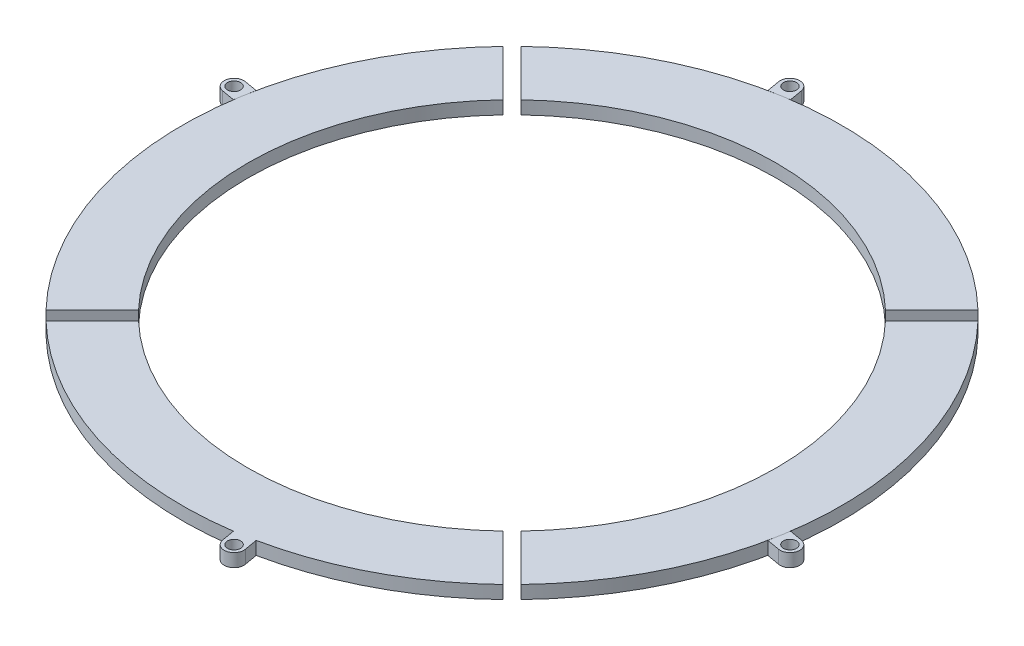
SolidWorks part; units mm, degrees
ref_plane "前视基准面" through (0, 0, 0) normal (0, 0, 1) x (1, 0, 0)
ref_plane "上视基准面" through (0, 0, 0) normal (0, 1, 0) x (1, 0, 0)
ref_plane "右视基准面" through (0, 0, 0) normal (1, 0, 0) x (0, 0, -1)
sketch "草图1" plane through (0, 0, 0) normal (0, 1, 0) x (1, 0, 0)
  line L0 (0, 28.5318) -> (0, -43.5615) construction
  line L1 (-12.686, 12.686) -> (30.0127, -30.0127) construction
  line L2 (0.7071, -0.7071) -> (71.4178, 70.0036)
  line L3 (71.4178, 70.0036) -> (70.0036, 71.4178)
  line L4 (70.0036, 71.4178) -> (-0.7071, 0.7071)
  line L5 (-0.7071, 0.7071) -> (0.7071, -0.7071)
  line L6 (0.7071, 0.7071) -> (-0.7071, -0.7071)
  line L7 (-0.7071, -0.7071) -> (70.0036, -71.4178)
  line L8 (70.0036, -71.4178) -> (71.4178, -70.0036)
  line L9 (71.4178, -70.0036) -> (0.7071, 0.7071)
  line L10 (0.7071, -0.7071) -> (-0.7071, 0.7071)
  line L11 (-0.7071, 0.7071) -> (-71.4178, -70.0036)
  line L12 (-71.4178, -70.0036) -> (-70.0036, -71.4178)
  line L13 (-70.0036, -71.4178) -> (0.7071, -0.7071)
  line L14 (-0.7071, -0.7071) -> (0.7071, 0.7071)
  line L15 (0.7071, 0.7071) -> (-70.0036, 71.4178)
  line L16 (-70.0036, 71.4178) -> (-71.4178, 70.0036)
  line L17 (-71.4178, 70.0036) -> (-0.7071, -0.7071)
  circle A0 centre (0, 0) radius 40.4
  circle A1 centre (0, 0) radius 50.4
  point P10 (0, 0)
  point P28 (0, 0)
  dimension "D2" = 80.8
  dimension "D3" = 100.8
  dimension "D1" = 45
  dimension "D4" = 100
  dimension "D5" = 2
  dimension "D6" = 4
extrude "凸台-拉伸1" add sketch "草图1" along normal blind 2 contours L17 A1 L11 A0 | L4 A1 L15 A0 | L9 A1 L2 A0 | L13 A1 L7 A0
sketch "草图2" plane through (0, 0, 0) normal (0, -1, 0) x (1, 0, 0)
  line L2 (0, 0) -> (9.0992, 51.6039) construction
  line L3 (10.2252, 49.3519) -> (7.2708, 49.8728)
  line L4 (8.3898, 8.3898) -> (0, 0) construction
  line L5 (27.8513, -29.2655) -> (29.2655, -27.8513) construction
  line L9 (0, 0) -> (10.8745, -10.8745) construction
  line L10 (7.2708, 49.8728) -> (7.622, 51.8644)
  line L17 (27.8513, 29.2655) -> (29.2655, 27.8513) construction
  line L18 (10.2252, 49.3519) -> (10.5764, 51.3435)
  line L19 (49.3519, 10.2252) -> (51.3435, 10.5764)
  line L20 (49.8728, 7.2708) -> (51.8644, 7.622)
  line L21 (49.3519, 10.2252) -> (49.8728, 7.2708)
  line L22 (-49.3519, -10.2252) -> (-51.3435, -10.5764)
  line L23 (-49.8728, -7.2708) -> (-51.8644, -7.622)
  line L24 (-49.3519, -10.2252) -> (-49.8728, -7.2708)
  line L25 (-10.2252, -49.3519) -> (-7.2708, -49.8728)
  line L26 (-7.2708, -49.8728) -> (-7.622, -51.8644)
  line L27 (-10.2252, -49.3519) -> (-10.5764, -51.3435)
  arc A2 (34.9241, 36.3383) -> (-34.9241, 36.3383) centre (0, 0) ccw construction
  arc A6 (-27.8513, -29.2655) -> (27.8513, -29.2655) centre (0, 0) ccw construction
  arc A7 (-27.8513, -29.2655) -> (27.8513, -29.2655) centre (0, 0) ccw construction
  arc A8 (34.9241, 36.3383) -> (-34.9241, 36.3383) centre (0, 0) ccw construction
  arc A9 (10.5764, 51.3435) -> (7.622, 51.8644) centre (9.0992, 51.6039) ccw
  circle A10 centre (9.0992, 51.6039) radius 1
  circle A11 centre (51.6039, 9.0992) radius 1
  arc A12 (51.3435, 10.5764) -> (51.8644, 7.622) centre (51.6039, 9.0992) cw
  circle A13 centre (-51.6039, -9.0992) radius 1
  arc A14 (-51.3435, -10.5764) -> (-51.8644, -7.622) centre (-51.6039, -9.0992) cw
  arc A15 (-10.5764, -51.3435) -> (-7.622, -51.8644) centre (-9.0992, -51.6039) ccw
  circle A16 centre (-9.0992, -51.6039) radius 1
  dimension "D1" = 2
  dimension "D4" = 52.4
  dimension "D2" = 1.5
  dimension "D3" = 35
extrude "凸台-拉伸2" add sketch "草图2" against normal up to surface (2 mm away) up to face at (0, 2, 39.1009)
